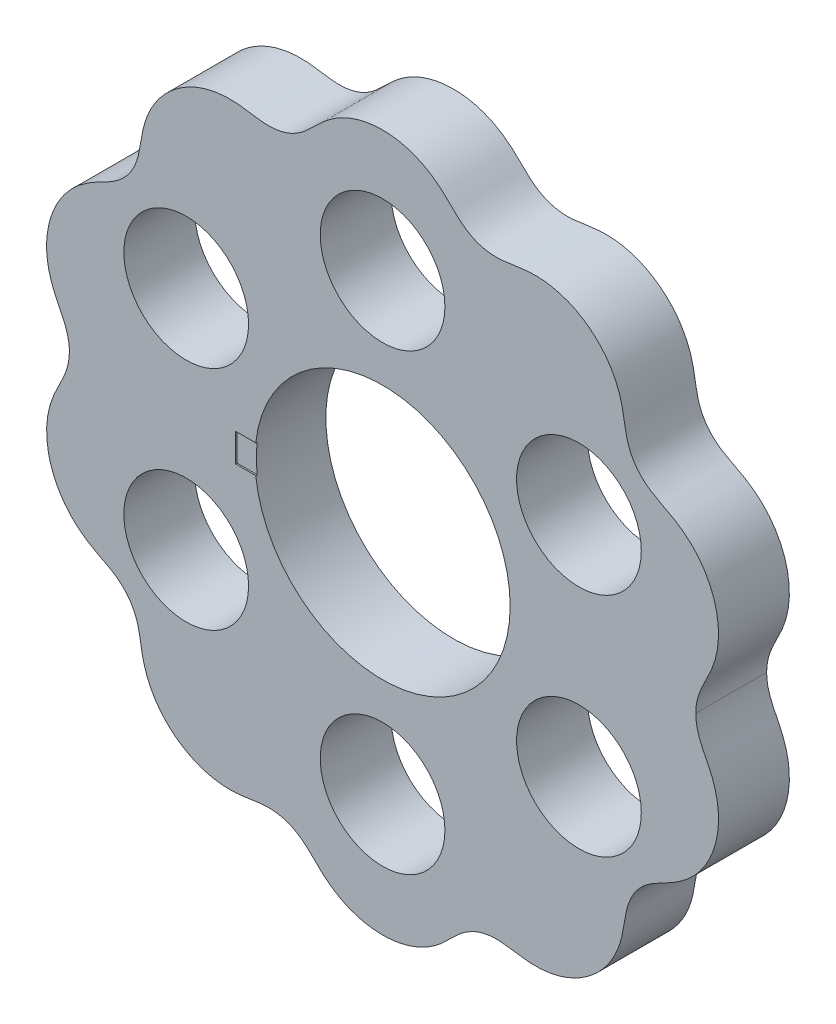
SolidWorks part; units mm, degrees
ref_plane "Front Plane" through (0, 0, 0) normal (0, 0, 1) x (1, 0, 0)
ref_plane "Top Plane" through (0, 0, 0) normal (0, 1, 0) x (1, 0, 0)
ref_plane "Right Plane" through (0, 0, 0) normal (1, 0, 0) x (0, 0, -1)
sketch "Sketch2" plane through (0, 0, -1165.0423) normal (0, 0, 1) x (1, 0, 0)
  line L0 (0, 0) -> (16, 0) construction
  circle A1 centre (0, 0) radius 9.0043
  circle A2 centre (13.8564, 8) radius 4.4
  circle A3 centre (13.8564, -8) radius 4.4
  circle A4 centre (0, -16) radius 4.4
  circle A5 centre (-13.8564, -8) radius 4.4
  circle A6 centre (-13.8564, 8) radius 4.4
  circle A7 centre (0, 16) radius 4.4
  spline S0 degree 4 poles (23.557, 7.0108) (23.5986, 6.8225) (23.6666, 6.4426) (23.7221, 5.8654) (23.7006, 5.0925) (23.5922, 4.3886) (23.4215, 3.7606) (23.2141, 3.209) (22.9937, 2.7289) (22.7529, 2.2591) (22.5466, 1.8458) (22.391, 1.4812) (22.2824, 1.1696) (22.2104, 0.9151) (22.1619, 0.6898) (22.1315, 0.4927) (22.1138, 0.3314) (22.1044, 0.199) (22.0995, 0.0431) (22.0996, -0.0366) (22.1028, -0.1505) (22.1078, -0.243) (22.113, -0.3136) (22.1212, -0.399) (22.1377, -0.5355) (22.1685, -0.7253) (22.222, -0.9617) (22.3011, -1.2285) (22.3962, -1.4893) (22.5046, -1.7453) (22.6227, -1.9965) (22.7467, -2.245) (22.8724, -2.4926) (22.9959, -2.7413) (23.1434, -3.0555) (23.3046, -3.4398) (23.4897, -3.9786) (23.651, -4.6834) (23.7301, -5.4867) (23.6901, -6.3763) (23.5267, -7.2454) (23.2469, -8.0784) (22.8584, -8.8593) (22.3699, -9.5758) (21.7468, -10.2595) (20.9798, -10.8802) (20.0719, -11.3935) (19.075, -11.857) (18.1814, -12.5254) (17.5226, -13.4352) (17.1659, -14.4991) (17.0352, -15.6021) (16.7731, -16.8502) (16.1832, -18.1698) (15.1853, -19.4264) (13.7589, -20.4568) (12.2578, -21.0093) (10.829, -21.1592) (9.5606, -21.0205) (8.461, -20.8021) (7.3284, -20.821) (6.2531, -21.1814) (5.3419, -21.8425) (4.5902, -22.6577) (3.6463, -23.5036) (2.4043, -24.213) (0.8726, -24.639) (-0.8726, -24.639) (-2.4043, -24.213) (-3.6463, -23.5036) (-4.5902, -22.6577) (-5.3419, -21.8425) (-6.2531, -21.1814) (-7.3284, -20.821) (-8.461, -20.8021) (-9.5606, -21.0205) (-10.829, -21.1592) (-12.2578, -21.0093) (-13.741, -20.4634) (-15.1394, -19.4615) (-16.0413, -18.3534) (-16.5535, -17.345) (-16.8193, -16.5384) (-16.9519, -15.9811) (-17.0719, -15.2755) (-17.1754, -14.568) (-17.3712, -13.8744) (-17.7598, -13.1055) (-18.3013, -12.4278) (-19.1201, -11.828) (-20.1618, -11.3541) (-21.2666, -10.702) (-22.3106, -9.734) (-23.1652, -8.4275) (-23.6256, -7.0174) (-23.7462, -5.7577) (-23.6634, -4.7771) (-23.5186, -4.0855) (-23.322, -3.4769) (-23.1003, -2.9486) (-22.8453, -2.4361) (-22.616, -1.991) (-22.4089, -1.5346) (-22.2772, -1.1634) (-22.2025, -0.8866) (-22.1548, -0.6409) (-22.1356, -0.5166) (-22.1225, -0.411) (-22.1138, -0.3229) (-22.1082, -0.2506) (-22.1041, -0.1747) (-22.1013, -0.0974) (-22.0996, -0.0136) (-22.1001, 0.0618) (-22.1044, 0.1995) (-22.1138, 0.3312) (-22.1315, 0.4927) (-22.1619, 0.6898) (-22.2104, 0.9151) (-22.2824, 1.1696) (-22.3693, 1.4188) (-22.4688, 1.6635) (-22.5782, 1.9037) (-22.6943, 2.1409) (-22.8135, 2.3764) (-22.9322, 2.6121) (-23.0764, 2.9089) (-23.2374, 3.2708) (-23.3876, 3.6703) (-23.5162, 4.109) (-23.627, 4.6149) (-23.7033, 5.1892) (-23.7194, 5.7688) (-23.6759, 6.3464) (-23.6156, 6.7276) (-23.5778, 6.9166) (-23.557, 7.0108) knots 0 0 0 0 0 0.00822 0.016439 0.024659 0.032878 0.038505 0.044131 0.049758 0.055384 0.061011 0.063824 0.066637 0.069451 0.072264 0.073671 0.075077 0.076484 0.077891 0.07937 0.08011 0.08085 0.08159 0.08233 0.08381 0.086769 0.089729 0.092688 0.095648 0.098607 0.101567 0.104526 0.107485 0.110445 0.113404 0.119323 0.125242 0.134701 0.144159 0.153617 0.163076 0.172284 0.181492 0.1907 0.199907 0.21162 0.223333 0.235045 0.246758 0.258596 0.270434 0.282272 0.294109 0.312776 0.331442 0.349816 0.36819 0.380136 0.392081 0.404027 0.415972 0.427792 0.439612 0.451432 0.463252 0.481626 0.5 0.518374 0.536748 0.548568 0.560388 0.572208 0.584028 0.595973 0.607919 0.619864 0.63181 0.650184 0.668558 0.686418 0.704279 0.710378 0.716478 0.722577 0.728677 0.740876 0.746976 0.753075 0.765274 0.777473 0.789672 0.801871 0.819732 0.837592 0.855453 0.864383 0.873313 0.879413 0.885512 0.891612 0.897711 0.903811 0.906861 0.91296 0.914485 0.91601 0.917535 0.918297 0.91906 0.919822 0.920585 0.921347 0.922109 0.923516 0.924923 0.926329 0.927736 0.930549 0.933363 0.936176 0.938989 0.941802 0.944616 0.947429 0.950242 0.953056 0.955869 0.961495 0.967122 0.971232 0.975341 0.983561 0.99178 0.99589 1 1 1 1 1 construction
  spline S1 degree 4 poles (22.1, 0) (22.1, -0.0293) (22.1007, -0.0733) (22.1028, -0.1505) (22.1078, -0.243) (22.113, -0.3136) (22.1212, -0.399) (22.1377, -0.5355) (22.1685, -0.7253) (22.222, -0.9617) (22.3011, -1.2285) (22.3962, -1.4893) (22.5046, -1.7453) (22.6227, -1.9965) (22.7467, -2.245) (22.8724, -2.4926) (22.9959, -2.7413) (23.1434, -3.0555) (23.3046, -3.4398) (23.4897, -3.9786) (23.651, -4.6834) (23.7301, -5.4867) (23.6901, -6.3763) (23.5267, -7.2454) (23.2469, -8.0784) (22.8584, -8.8593) (22.3699, -9.5758) (21.7468, -10.2595) (20.9798, -10.8802) (20.0719, -11.3935) (19.075, -11.857) (18.1814, -12.5254) (17.5226, -13.4352) (17.1659, -14.4991) (17.0352, -15.6021) (16.7731, -16.8502) (16.1832, -18.1698) (15.1853, -19.4264) (13.7589, -20.4568) (12.2578, -21.0093) (10.829, -21.1592) (9.5606, -21.0205) (8.461, -20.8021) (7.3284, -20.821) (6.2531, -21.1814) (5.3419, -21.8425) (4.5902, -22.6577) (3.6463, -23.5036) (2.4043, -24.213) (0.8726, -24.639) (-0.8726, -24.639) (-2.4043, -24.213) (-3.6463, -23.5036) (-4.5902, -22.6577) (-5.3419, -21.8425) (-6.2531, -21.1814) (-7.3284, -20.821) (-8.461, -20.8021) (-9.5606, -21.0205) (-10.829, -21.1592) (-12.2578, -21.0093) (-13.741, -20.4634) (-15.1394, -19.4615) (-16.0413, -18.3534) (-16.5535, -17.345) (-16.8193, -16.5384) (-16.9519, -15.9811) (-17.0719, -15.2755) (-17.1754, -14.568) (-17.3712, -13.8744) (-17.7598, -13.1055) (-18.3013, -12.4278) (-19.1201, -11.828) (-20.1618, -11.3541) (-21.2666, -10.702) (-22.3106, -9.734) (-23.1652, -8.4275) (-23.6256, -7.0174) (-23.7462, -5.7577) (-23.6634, -4.7771) (-23.5186, -4.0855) (-23.322, -3.4769) (-23.1003, -2.9486) (-22.8453, -2.4361) (-22.616, -1.991) (-22.4089, -1.5346) (-22.2772, -1.1634) (-22.2025, -0.8866) (-22.1548, -0.6409) (-22.1356, -0.5166) (-22.1225, -0.411) (-22.1138, -0.3229) (-22.1082, -0.2506) (-22.1041, -0.1747) (-22.1013, -0.0974) (-22.1002, -0.0455) (-22.1, -0.0151) (-22.1, 0) knots 0.077891 0.077891 0.077891 0.077891 0.077891 0.07937 0.08011 0.08085 0.08159 0.08233 0.08381 0.086769 0.089729 0.092688 0.095648 0.098607 0.101567 0.104526 0.107485 0.110445 0.113404 0.119323 0.125242 0.134701 0.144159 0.153617 0.163076 0.172284 0.181492 0.1907 0.199907 0.21162 0.223333 0.235045 0.246758 0.258596 0.270434 0.282272 0.294109 0.312776 0.331442 0.349816 0.36819 0.380136 0.392081 0.404027 0.415972 0.427792 0.439612 0.451432 0.463252 0.481626 0.5 0.518374 0.536748 0.548568 0.560388 0.572208 0.584028 0.595973 0.607919 0.619864 0.63181 0.650184 0.668558 0.686418 0.704279 0.710378 0.716478 0.722577 0.728677 0.740876 0.746976 0.753075 0.765274 0.777473 0.789672 0.801871 0.819732 0.837592 0.855453 0.864383 0.873313 0.879413 0.885512 0.891612 0.897711 0.903811 0.906861 0.91296 0.914485 0.91601 0.917535 0.918297 0.91906 0.919822 0.920585 0.921347 0.922109 0.922109 0.922109 0.922109 0.922109
  spline S2 degree 4 poles (22.1, 0) (22.1, 0.0293) (22.1007, 0.0733) (22.1028, 0.1505) (22.1078, 0.243) (22.113, 0.3136) (22.1212, 0.399) (22.1377, 0.5355) (22.1685, 0.7253) (22.222, 0.9617) (22.3011, 1.2285) (22.3962, 1.4893) (22.5046, 1.7453) (22.6227, 1.9965) (22.7467, 2.245) (22.8724, 2.4926) (22.9959, 2.7413) (23.1434, 3.0555) (23.3046, 3.4398) (23.4897, 3.9786) (23.651, 4.6834) (23.7301, 5.4867) (23.6901, 6.3763) (23.5267, 7.2454) (23.2469, 8.0784) (22.8584, 8.8593) (22.3699, 9.5758) (21.7468, 10.2595) (20.9798, 10.8802) (20.0719, 11.3935) (19.075, 11.857) (18.1814, 12.5254) (17.5226, 13.4352) (17.1659, 14.4991) (17.0352, 15.6021) (16.7731, 16.8502) (16.1832, 18.1698) (15.1853, 19.4264) (13.7589, 20.4568) (12.2578, 21.0093) (10.829, 21.1592) (9.5606, 21.0205) (8.461, 20.8021) (7.3284, 20.821) (6.2531, 21.1814) (5.3419, 21.8425) (4.5902, 22.6577) (3.6463, 23.5036) (2.4043, 24.213) (0.8726, 24.639) (-0.8726, 24.639) (-2.4043, 24.213) (-3.6463, 23.5036) (-4.5902, 22.6577) (-5.3419, 21.8425) (-6.2531, 21.1814) (-7.3284, 20.821) (-8.461, 20.8021) (-9.5606, 21.0205) (-10.829, 21.1592) (-12.2578, 21.0093) (-13.741, 20.4634) (-15.1394, 19.4615) (-16.0413, 18.3534) (-16.5535, 17.345) (-16.8193, 16.5384) (-16.9519, 15.9811) (-17.0719, 15.2755) (-17.1754, 14.568) (-17.3712, 13.8744) (-17.7598, 13.1055) (-18.3013, 12.4278) (-19.1201, 11.828) (-20.1618, 11.3541) (-21.2666, 10.702) (-22.3106, 9.734) (-23.1652, 8.4275) (-23.6256, 7.0174) (-23.7462, 5.7577) (-23.6634, 4.7771) (-23.5186, 4.0855) (-23.322, 3.4769) (-23.1003, 2.9486) (-22.8453, 2.4361) (-22.616, 1.991) (-22.4089, 1.5346) (-22.2772, 1.1634) (-22.2025, 0.8866) (-22.1548, 0.6409) (-22.1356, 0.5166) (-22.1225, 0.411) (-22.1138, 0.3229) (-22.1082, 0.2506) (-22.1041, 0.1747) (-22.1013, 0.0974) (-22.1002, 0.0455) (-22.1, 0.0151) (-22.1, 0) knots 0.077891 0.077891 0.077891 0.077891 0.077891 0.07937 0.08011 0.08085 0.08159 0.08233 0.08381 0.086769 0.089729 0.092688 0.095648 0.098607 0.101567 0.104526 0.107485 0.110445 0.113404 0.119323 0.125242 0.134701 0.144159 0.153617 0.163076 0.172284 0.181492 0.1907 0.199907 0.21162 0.223333 0.235045 0.246758 0.258596 0.270434 0.282272 0.294109 0.312776 0.331442 0.349816 0.36819 0.380136 0.392081 0.404027 0.415972 0.427792 0.439612 0.451432 0.463252 0.481626 0.5 0.518374 0.536748 0.548568 0.560388 0.572208 0.584028 0.595973 0.607919 0.619864 0.63181 0.650184 0.668558 0.686418 0.704279 0.710378 0.716478 0.722577 0.728677 0.740876 0.746976 0.753075 0.765274 0.777473 0.789672 0.801871 0.819732 0.837592 0.855453 0.864383 0.873313 0.879413 0.885512 0.891612 0.897711 0.903811 0.906861 0.91296 0.914485 0.91601 0.917535 0.918297 0.91906 0.919822 0.920585 0.921347 0.922109 0.922109 0.922109 0.922109 0.922109
  point P22 (0, 0)
  dimension "D1" = 6
extrude "Boss-Extrude1" add sketch "Sketch2" against normal blind 5
sketch "Sketch3" plane through (0, 0, -1165.0423) normal (0, 0, 1) x (1, 0, 0)
  line L0 (-9.0043, 0) -> (-10.3888, 0) construction
  line L1 (-10.3888, -1) -> (-10.3888, 1)
  line L2 (-10.3888, 1) -> (-8.7429, 1)
  line L3 (-10.3888, -1) -> (-8.6639, -1)
  line L4 (-8.6639, -1) -> (-8.6639, 1)
  line L5 (-8.6639, 1) -> (-8.7429, 1)
  circle A0 centre (0, 0) radius 9.0043 construction
extrude "Cut-Extrude1" cut sketch "Sketch3" against normal blind 0.1
